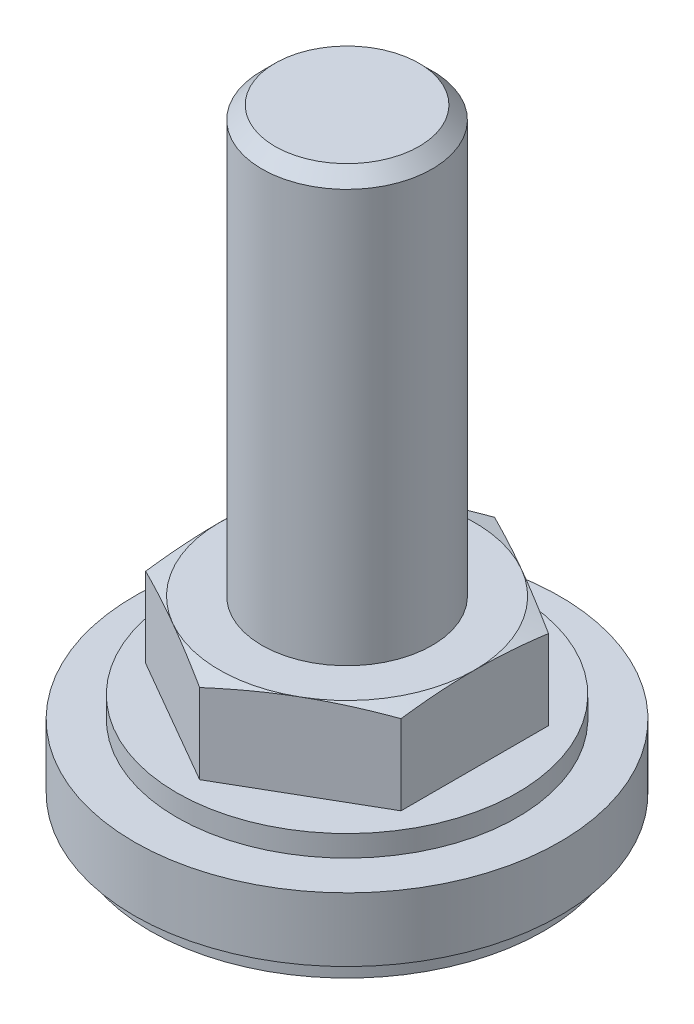
SolidWorks part; units mm, degrees
ref_plane "Front Plane" through (0, 0, 0) normal (0, 0, 1) x (1, 0, 0)
ref_plane "Top Plane" through (0, 0, 0) normal (0, 1, 0) x (1, 0, 0)
ref_plane "Right Plane" through (0, 0, 0) normal (1, 0, 0) x (0, 0, -1)
ref_plane "Plane1" through (0, 0, 0) normal (0, 0, 1) x (1, 0, 0)
sketch "Sketch1" plane through (0, 0, 0) normal (0, 0, 1) x (1, 0, 0)
  line L0 (0, 50) -> (6.773, 50)
  line L1 (6.773, 50) -> (8, 48.773)
  line L2 (8, 48.773) -> (8, 10)
  line L3 (8, 10) -> (12, 10)
  line L4 (12, 10) -> (15, 9.1962)
  line L5 (15, 9.1962) -> (15, 2)
  line L6 (15, 2) -> (16, 2)
  line L7 (16, 2) -> (16, 0)
  line L8 (16, 0) -> (20, 0)
  line L9 (20, 0) -> (20, -6)
  line L10 (20, -6) -> (18.5, -6)
  line L11 (18.5, -6) -> (18.5, -8)
  line L12 (18.5, -8) -> (0, -8)
  line L13 (0, -8) -> (0, 50)
  line L14 (0, -8) -> (0, 50) construction
revolve "Revolve1" add sketch "Sketch1" angle 360 about L14
ref_plane "Plane2" through (0, 2, 0) normal (0, 1, 0) x (1, 0, 0)
sketch "Sketch2" plane through (0, 2, 0) normal (0, 1, 0) x (1, 0, 0)
  line L0 (-12, 6.9282) -> (-12, -6.9282)
  line L1 (-12, -6.9282) -> (0, -13.8564)
  line L2 (0, -13.8564) -> (12, -6.9282)
  line L3 (12, -6.9282) -> (12, 6.9282)
  line L4 (12, 6.9282) -> (0, 13.8564)
  line L5 (0, 13.8564) -> (-12, 6.9282)
  circle A0 centre (0, 0) radius 17
extrude "Cut-Extrude1" cut sketch "Sketch2" along normal blind 10
